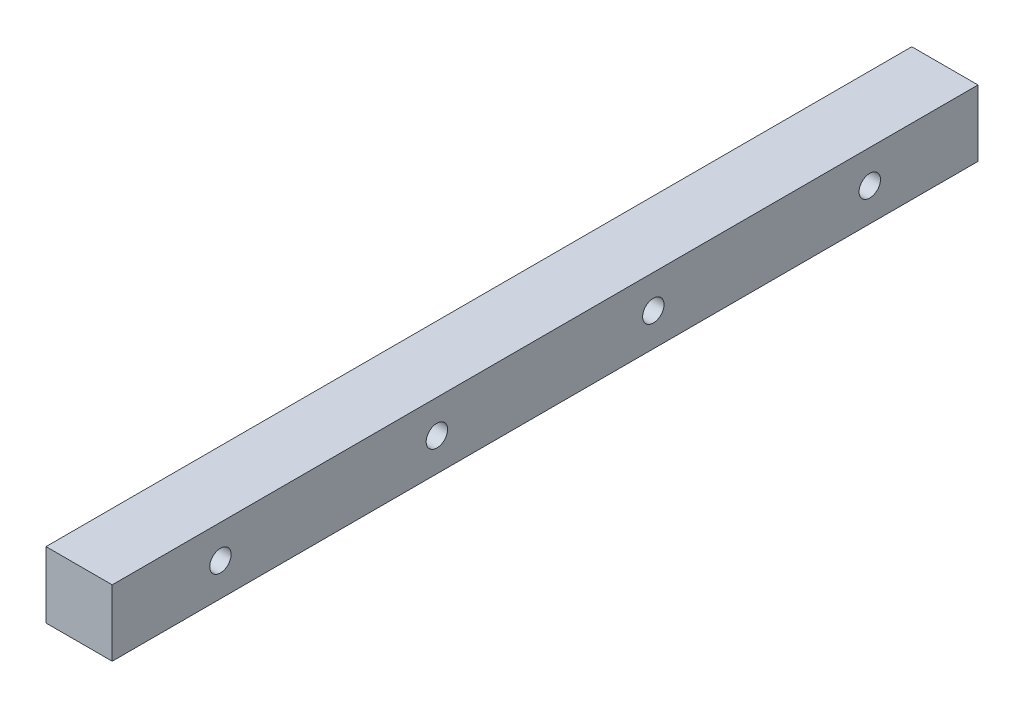
SolidWorks part; units mm, degrees
ref_plane "Front Plane" through (0, 0, 0) normal (0, 0, 1) x (1, 0, 0)
ref_plane "Top Plane" through (0, 0, 0) normal (0, 1, 0) x (1, 0, 0)
ref_plane "Right Plane" through (0, 0, 0) normal (1, 0, 0) x (0, 0, -1)
sketch "Sketch1" plane through (0, 0, 0) normal (0, 0, 1) x (1, 0, 0)
  line L0 (-6.5, -6.5) -> (6.5, -6.5)
  line L1 (6.5, -6.5) -> (6.5, 6.5)
  line L2 (6.5, 6.5) -> (-6.5, 6.5)
  line L3 (-6.5, 6.5) -> (-6.5, -6.5)
extrude "Boss-Extrude1" add sketch "Sketch1" along normal mid plane 170
sketch "Sketch2" plane through (0, 0, 0) normal (1, 0, 0) x (0, 0, -1)
  circle A0 centre (63.75, 0) radius 2.1
  circle A1 centre (21.25, 0) radius 2.1
  circle A2 centre (-21.25, 0) radius 2.1
  circle A3 centre (-63.75, 0) radius 2.1
extrude "Cut-Extrude1" cut sketch "Sketch2" against normal mid plane 23
ref_plane "Plane1" through (-6.5, 0, 0) normal (1, 0, 0) x (0, 0, -1)
sketch "Sketch3" plane through (-6.5, 0, 0) normal (1, 0, 0) x (0, 0, -1)
  circle A0 centre (63.75, 0) radius 5.25
  circle A1 centre (21.25, 0) radius 5.25
  circle A2 centre (-21.25, 0) radius 5.25
  circle A3 centre (-63.75, 0) radius 5.25
extrude "Cut-Extrude2" cut sketch "Sketch3" against normal mid plane 9
